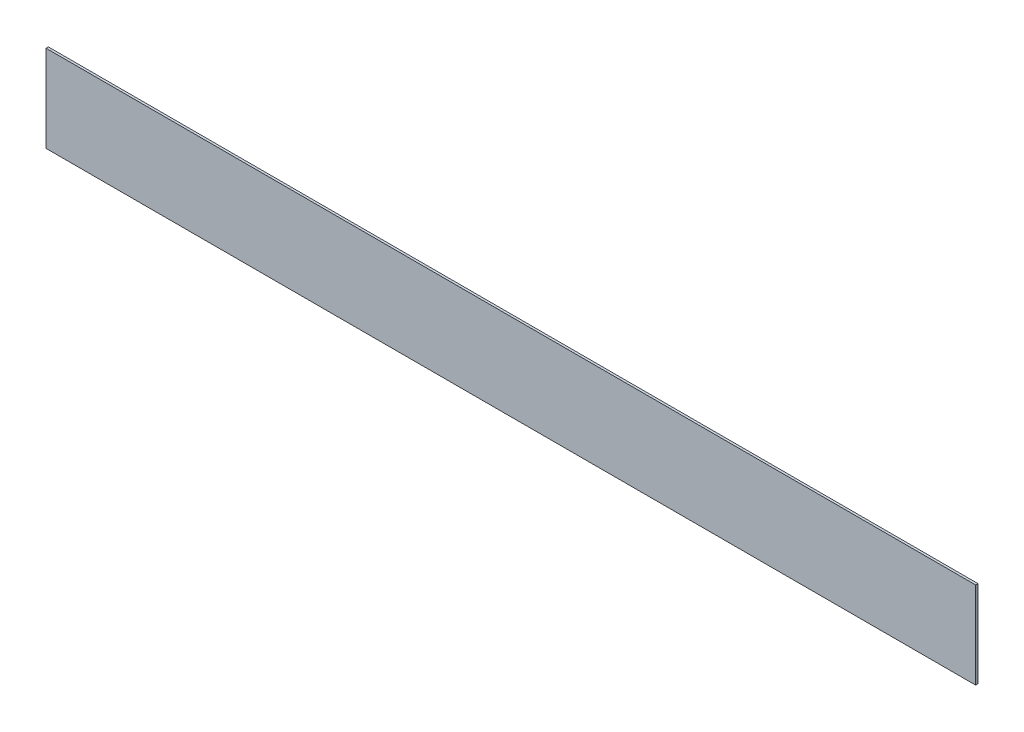
SolidWorks part; units mm, degrees
ref_plane "Front Plane" through (0, 0, 0) normal (0, 0, 1) x (1, 0, 0)
ref_plane "Top Plane" through (0, 0, 0) normal (0, 1, 0) x (1, 0, 0)
ref_plane "Right Plane" through (0, 0, 0) normal (1, 0, 0) x (0, 0, -1)
sketch "Sketch1" plane through (0, 0, 0) normal (0, 0, 1) x (1, 0, 0)
  line L1 (-457.2, 42.672) -> (457.2, 42.672)
  line L2 (-457.2, 42.672) -> (-457.2, -42.672)
  line L3 (-457.2, -42.672) -> (457.2, -42.672)
  line L4 (457.2, 42.672) -> (457.2, -42.672)
  line L5 (-457.2, 42.672) -> (457.2, -42.672) construction
  line L6 (-457.2, -42.672) -> (457.2, 42.672) construction
  point P0 (0, 0)
extrude "Boss-Extrude1" add sketch "Sketch1" along normal mid plane 2.286
